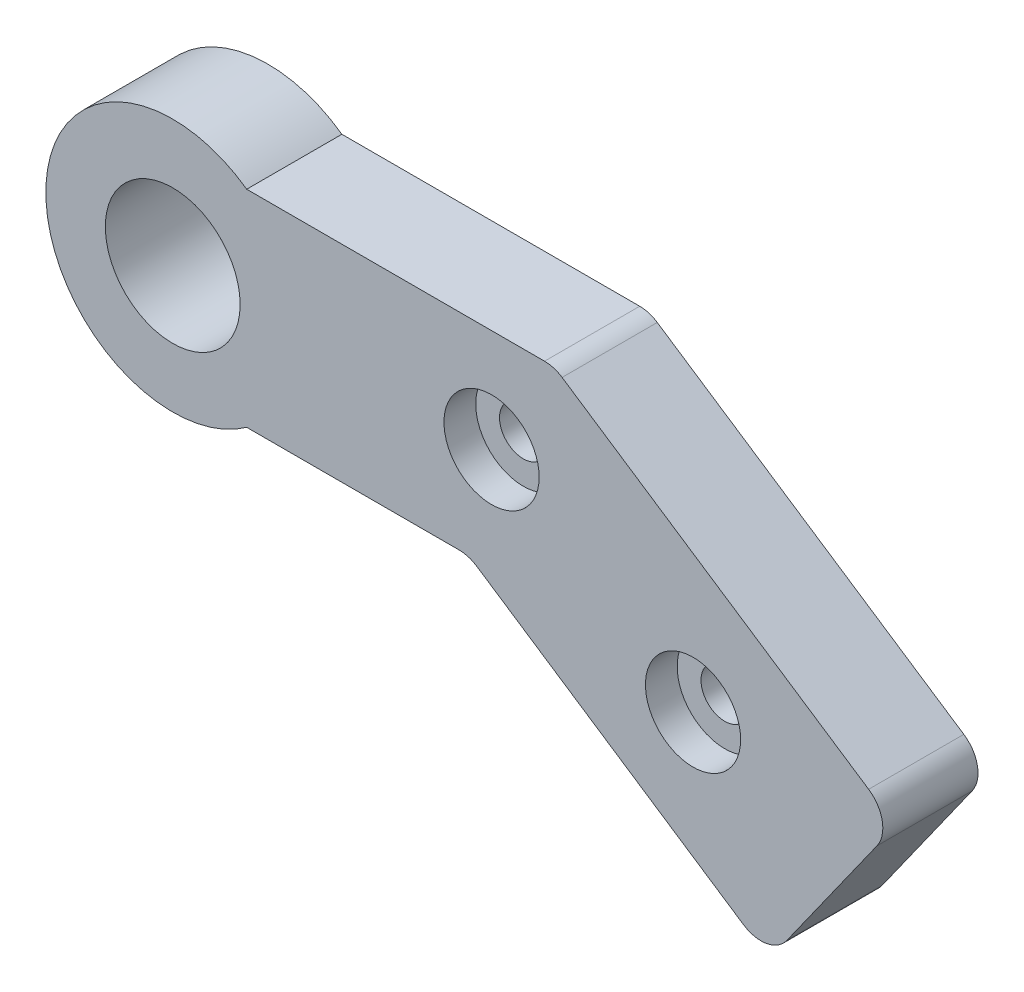
SolidWorks part; units mm, degrees
ref_plane "Plan de face" through (0, 0, 0) normal (0, 0, 1) x (1, 0, 0)
ref_plane "Plan de dessus" through (0, 0, 0) normal (0, 1, 0) x (1, 0, 0)
ref_plane "Plan de droite" through (0, 0, 0) normal (1, 0, 0) x (0, 0, -1)
sketch "Esquisse1" plane through (0, 0, 0) normal (0, 0, 1) x (1, 0, 0)
  line L0 (2.6679, 5.6573) -> (4.7324, 3.5928) construction
  line L1 (-16.7121, 5.6573) -> (2.6679, 5.6573)
  line L3 (-16.7121, -7.3427) -> (-2.7121, -7.3427)
  line L4 (-27.299, -0.8427) -> (21.5919, -0.8427) construction
  line L7 (2.6679, 5.6573) -> (24.215, -8.641)
  line L8 (-2.7121, -7.3427) -> (16.2195, -19.9053)
  line L9 (24.215, -8.641) -> (16.2195, -19.9053)
  arc A0 (-16.7121, 5.6573) -> (-16.7121, -7.3427) centre (-21.3758, -0.8427) ccw
  point P0 (0, 0)
  dimension "D6" = 8
  dimension "D1" = 13
  dimension "D2" = 45
  dimension "D3" = 14
  dimension "D4" = 19.38
extrude "Boss.-Extru.1" add sketch "Esquisse1" along normal blind 6
fillet "Congé1" radius 2 4 edges at (24.215, -8.641, 3) (16.2195, -19.9053, 3) (-2.7121, -7.3427, 3) (2.6679, 5.6573, 3)
sketch "Esquisse2" plane through (0, 0, 6) normal (0, 0, 1) x (1, 0, 0)
  line L0 (-1.2758, -0.8427) -> (20.1809, -14.3244) construction
  line L2 (-43.7586, -0.8427) -> (6.2431, -0.8427) construction
  line L4 (-17.7116, 6.2689) -> (-25.0399, -7.9542) construction
  line L5 (17.3413, -18.3249) -> (23.0204, -10.3239) construction
  circle A0 centre (-21.3758, -0.8427) radius 4.25
  circle A1 centre (-1.2758, -0.8427) radius 1.5
  circle A2 centre (11.4252, -8.823) radius 1.5
  arc A3 (-16.7121, 5.6573) -> (-16.7121, -7.3427) centre (-21.3758, -0.8427) ccw construction
  dimension "D1" = 8.5
  dimension "D2" = 3
  dimension "D4" = 3
  dimension "D5" = 20.1
  dimension "D6" = 15
extrude "Enlèv. mat.-Extru.1" cut sketch "Esquisse2" against normal through all
sketch "Esquisse3" plane through (0, 0, 6) normal (0, 0, 1) x (1, 0, 0)
  circle A0 centre (-1.2758, -0.8427) radius 3
  circle A1 centre (11.4252, -8.823) radius 3
  dimension "D1" = 6
  dimension "D2" = 6
extrude "Enlèv. mat.-Extru.2" cut sketch "Esquisse3" against normal blind 2
